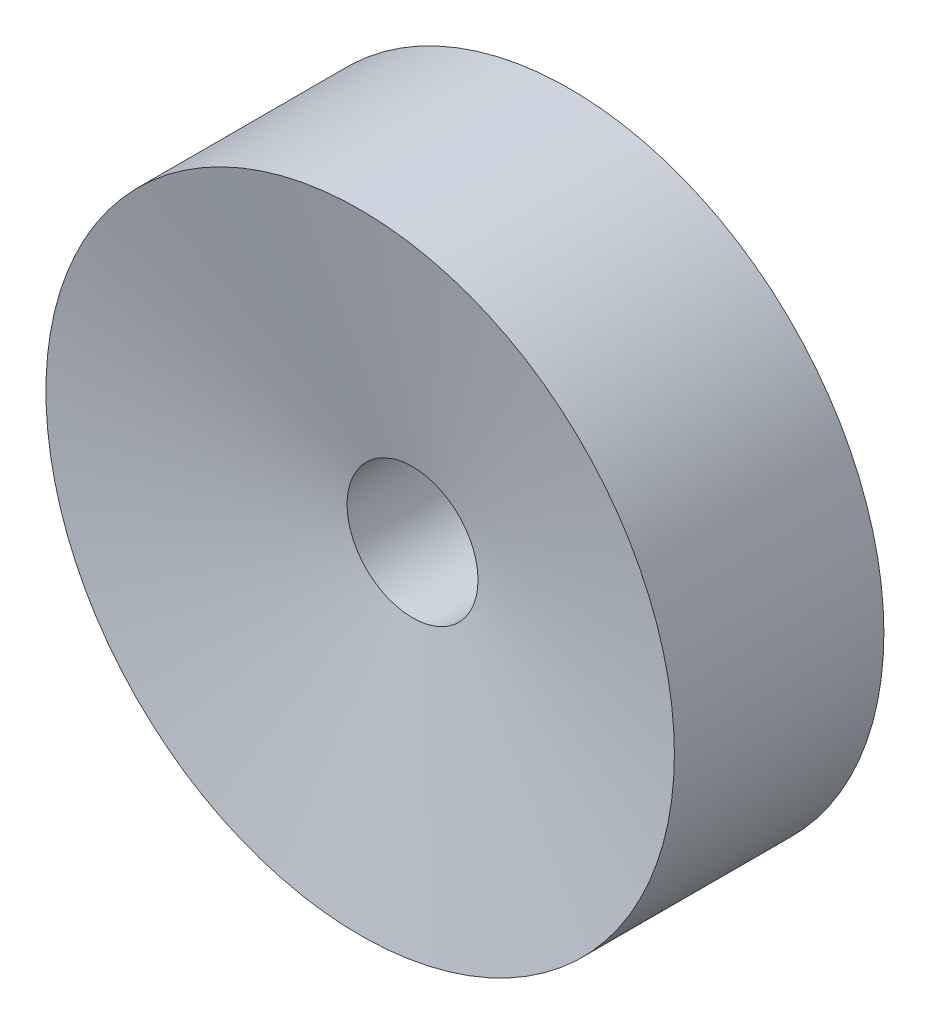
SolidWorks part; units mm, degrees
material "Custom Plastic"
ref_plane "Front Plane" through (0, 0, 0) normal (0, 0, 1) x (1, 0, 0)
ref_plane "Top Plane" through (0, 0, 0) normal (0, 1, 0) x (1, 0, 0)
ref_plane "Right Plane" through (0, 0, 0) normal (1, 0, 0) x (0, 0, -1)
sketch "Sketch2" plane through (0, 0, 0) normal (1, 0, 0) x (0, 0, -1)
  line L0 (12.7, 15.875) -> (-12.7, 15.875)
  line L1 (-12.7, 15.875) -> (-25.4, 76.2)
  line L2 (-25.4, 76.2) -> (25.4, 76.2)
  line L3 (0, 15.875) -> (0, 76.2) construction
  line L4 (12.7, 15.875) -> (25.4, 76.2)
  line L5 (-9.9465, 0) -> (20.5879, 0) construction
  dimension "D1" = 15.875
  dimension "D2" = 12.7
  dimension "D3" = 60.325
  dimension "D4" = 12.7
revolve "Revolve1" add sketch "Sketch2" angle 360 about L5
